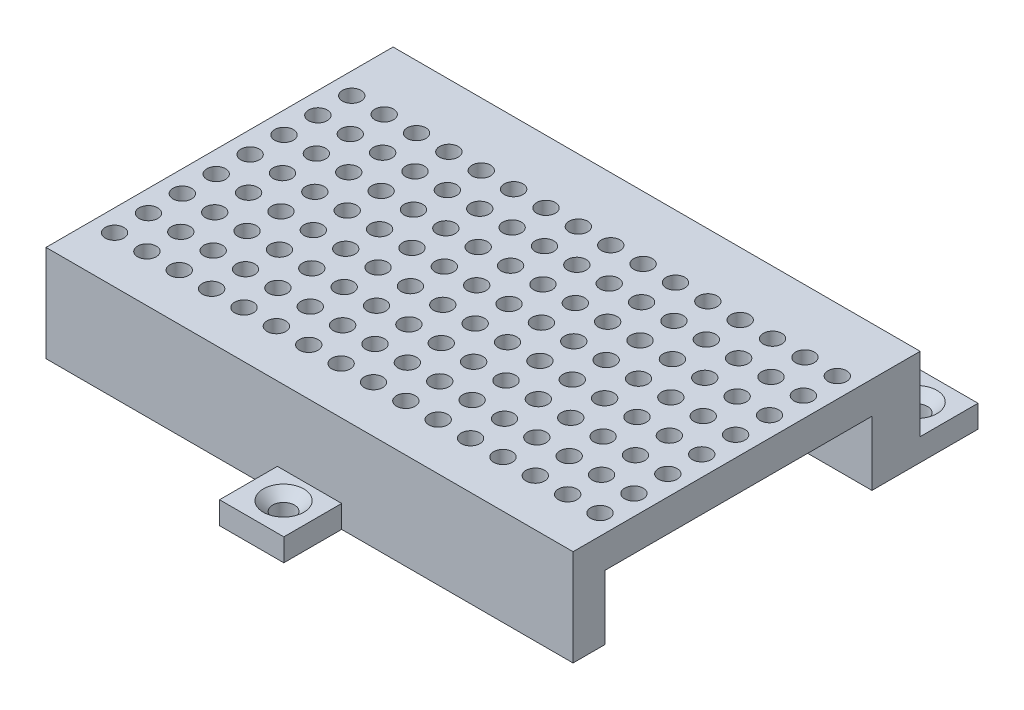
SolidWorks part; units mm, degrees
ref_plane "Plan de face" through (0, 0, 0) normal (0, 0, 1) x (1, 0, 0)
ref_plane "Plan de dessus" through (0, 0, 0) normal (0, 1, 0) x (1, 0, 0)
ref_plane "Plan de droite" through (0, 0, 0) normal (1, 0, 0) x (0, 0, -1)
sketch "Esquisse1" plane through (0, 0, 0) normal (0, 1, 0) x (1, 0, 0)
  line L1 (-43.2753, 24.8362) -> (38.7247, 24.8362)
  line L2 (-43.2753, 24.8362) -> (-43.2753, -29.1638)
  line L3 (-43.2753, -29.1638) -> (38.7247, -29.1638)
  line L4 (38.7247, 24.8362) -> (38.7247, -29.1638)
  dimension "D1" = 54
  dimension "D2" = 82
extrude "Boss.-Extru.1" add sketch "Esquisse1" along normal blind 5
sketch "Esquisse2" plane through (0, 0, 29.1638) normal (0, 0, 1) x (1, 0, 0)
  line L0 (-43.2753, 5) -> (38.7247, 5)
  line L1 (-43.2753, 5) -> (-43.2753, -10)
  line L2 (38.7247, 5) -> (38.7247, -10)
  line L3 (-43.2753, -10) -> (38.7247, -10)
  dimension "D1" = 15
extrude "Boss.-Extru.2" add sketch "Esquisse2" against normal blind 5
sketch "Esquisse3" plane through (0, 0, 0) normal (0, -1, 0) x (1, 0, 0)
  line L1 (-43.2753, -24.8362) -> (-33.2753, -24.8362)
  line L2 (-43.2753, -24.8362) -> (-43.2753, -17.3362)
  line L3 (-43.2753, -17.3362) -> (-33.2753, -17.3362)
  line L4 (-33.2753, -24.8362) -> (-33.2753, -17.3362)
  line L5 (38.7247, -24.8362) -> (28.7247, -24.8362)
  line L6 (38.7247, -24.8362) -> (38.7247, -17.3362)
  line L7 (38.7247, -17.3362) -> (28.7247, -17.3362)
  line L8 (28.7247, -24.8362) -> (28.7247, -17.3362)
  dimension "D1" = 7.5
  dimension "D2" = 10
  dimension "D3" = 7.5
  dimension "D4" = 10
extrude "Boss.-Extru.3" add sketch "Esquisse3" along normal blind 10
sketch "Esquisse4" plane through (0, 0, -24.8362) normal (0, 0, -1) x (-1, 0, 0)
  line L0 (-28.7247, -10) -> (-28.7247, 0) construction
  line L1 (-38.7247, -10) -> (-28.7247, -10)
  line L2 (-38.7247, -10) -> (-38.7247, -6.5)
  line L3 (-38.7247, -6.5) -> (-28.7247, -6.5)
  line L4 (-28.7247, -10) -> (-28.7247, -6.5)
  line L5 (33.2753, -10) -> (33.2753, 0) construction
  line L6 (43.2753, -10) -> (33.2753, -10)
  line L7 (43.2753, -10) -> (43.2753, -6.5)
  line L8 (43.2753, -6.5) -> (33.2753, -6.5)
  line L9 (33.2753, -10) -> (33.2753, -6.5)
  dimension "D1" = 3.5
  dimension "D2" = 3.5
extrude "Boss.-Extru.4" add sketch "Esquisse4" along normal blind 9
hole_wizard "Fraisage pour vis à tête fraisée M31" positions "Esquisse5" profile "Esquisse6" countersink size "M3" standard "ISO" end condition through all
sketch "Esquisse5" plane through (0, -6.5, 0) normal (0, 1, 0) x (1, 0, 0)
  point P0 (-38.4178, 29.233)
  point P2 (33.7833, 29.233)
sketch "Esquisse6" plane through (-38.4178, -6.5, -29.233) normal (1, 0, 0) x (0, 0, 1)
  line L0 (0, 0) -> (0, 3.5)
  line L1 (0, 3.5) -> (1.7, 3.5)
  line L2 (1.7, 3.5) -> (1.7, 1.45)
  line L3 (1.7, 1.45) -> (3.15, 0)
  line L5 (3.15, 0) -> (0, 0)
  line L6 (-1.7, 1.45) -> (-3.15, 0) construction
  line L11 (0, -6.35) -> (0, 107.95) construction
  dimension "Diamètre du perçage jusqu'au prochain" = 3.4
  dimension "Profondeur du perçage jusqu'au prochain" = 3.5
  dimension "Diamètre du fraisage entrant" = 6.3
  dimension "Angle du fraisage entrant" = 90
sketch "Esquisse7" plane through (0, 0, 29.1638) normal (0, 0, 1) x (1, 0, 0)
  line L1 (-43.2753, -10) -> (38.7247, -10) construction
  line L2 (38.7247, 5) -> (38.7247, -10) construction
  line L3 (-7.2753, -10) -> (2.7247, -10)
  line L4 (-7.2753, -10) -> (-7.2753, -6.5)
  line L5 (-7.2753, -6.5) -> (2.7247, -6.5)
  line L6 (2.7247, -10) -> (2.7247, -6.5)
  point P0 (-2.2753, -10)
  dimension "D1" = 36
  dimension "D2" = 10
  dimension "D3" = 3.5
extrude "Boss.-Extru.5" add sketch "Esquisse7" along normal blind 9
hole_wizard "Fraisage pour vis à tête fraisée M32" positions "Esquisse8" profile "Esquisse9" countersink size "M3" standard "ISO" end condition through all
sketch "Esquisse8" plane through (0, -6.5, 0) normal (0, 1, 0) x (1, 0, 0)
  point P0 (-2.1798, -33.2996)
sketch "Esquisse9" plane through (-2.1798, -6.5, 33.2996) normal (1, 0, 0) x (0, 0, 1)
  line L0 (0, 0) -> (0, 3.5)
  line L1 (0, 3.5) -> (1.7, 3.5)
  line L2 (1.7, 3.5) -> (1.7, 1.45)
  line L3 (1.7, 1.45) -> (3.15, 0)
  line L5 (3.15, 0) -> (0, 0)
  line L6 (-1.7, 1.45) -> (-3.15, 0) construction
  line L11 (0, -6.35) -> (0, 107.95) construction
  dimension "Diamètre du perçage jusqu'au prochain" = 3.4
  dimension "Profondeur du perçage jusqu'au prochain" = 3.5
  dimension "Diamètre du fraisage entrant" = 6.3
  dimension "Angle du fraisage entrant" = 90
sketch "Esquisse10" plane through (0, 5, 0) normal (0, 1, 0) x (1, 0, 0)
  circle A0 centre (-39.9169, 15.0522) radius 1.4509
  circle A1 centre (-34.8813, 15.0522) radius 1.4509
  circle A2 centre (-29.8456, 15.0522) radius 1.4509
  circle A3 centre (-24.81, 15.0522) radius 1.4509
  circle A4 centre (-19.7744, 15.0522) radius 1.4509
  circle A5 centre (-14.7388, 15.0522) radius 1.4509
  circle A6 centre (-9.7032, 15.0522) radius 1.4509
  circle A7 centre (-4.6675, 15.0522) radius 1.4509
  circle A8 centre (0.3681, 15.0522) radius 1.4509
  circle A9 centre (5.4037, 15.0522) radius 1.4509
  circle A10 centre (10.4393, 15.0522) radius 1.4509
  circle A11 centre (15.4749, 15.0522) radius 1.4509
  circle A12 centre (20.5106, 15.0522) radius 1.4509
  circle A13 centre (25.5462, 15.0522) radius 1.4509
  circle A14 centre (30.5818, 15.0522) radius 1.4509
  circle A15 centre (35.6174, 15.0522) radius 1.4509
  circle A16 centre (-34.8813, 9.7792) radius 1.4509
  circle A17 centre (-29.8456, 9.7792) radius 1.4509
  circle A18 centre (-24.81, 9.7792) radius 1.4509
  circle A19 centre (-19.7744, 9.7792) radius 1.4509
  circle A20 centre (-14.7388, 9.7792) radius 1.4509
  circle A21 centre (-9.7032, 9.7792) radius 1.4509
  circle A22 centre (-4.6675, 9.7792) radius 1.4509
  circle A23 centre (0.3681, 9.7792) radius 1.4509
  circle A24 centre (5.4037, 9.7792) radius 1.4509
  circle A25 centre (10.4393, 9.7792) radius 1.4509
  circle A26 centre (15.4749, 9.7792) radius 1.4509
  circle A27 centre (20.5106, 9.7792) radius 1.4509
  circle A28 centre (25.5462, 9.7792) radius 1.4509
  circle A29 centre (30.5818, 9.7792) radius 1.4509
  circle A30 centre (35.6174, 9.7792) radius 1.4509
  circle A31 centre (-34.8813, 4.5062) radius 1.4509
  circle A32 centre (-29.8456, 4.5062) radius 1.4509
  circle A33 centre (-24.81, 4.5062) radius 1.4509
  circle A34 centre (-19.7744, 4.5062) radius 1.4509
  circle A35 centre (-14.7388, 4.5062) radius 1.4509
  circle A36 centre (-9.7032, 4.5062) radius 1.4509
  circle A37 centre (-4.6675, 4.5062) radius 1.4509
  circle A38 centre (0.3681, 4.5062) radius 1.4509
  circle A39 centre (5.4037, 4.5062) radius 1.4509
  circle A40 centre (10.4393, 4.5062) radius 1.4509
  circle A41 centre (15.4749, 4.5062) radius 1.4509
  circle A42 centre (20.5106, 4.5062) radius 1.4509
  circle A43 centre (25.5462, 4.5062) radius 1.4509
  circle A44 centre (30.5818, 4.5062) radius 1.4509
  circle A45 centre (35.6174, 4.5062) radius 1.4509
  circle A46 centre (-34.8813, -0.7668) radius 1.4509
  circle A47 centre (-29.8456, -0.7668) radius 1.4509
  circle A48 centre (-24.81, -0.7668) radius 1.4509
  circle A49 centre (-19.7744, -0.7668) radius 1.4509
  circle A50 centre (-14.7388, -0.7668) radius 1.4509
  circle A51 centre (-9.7032, -0.7668) radius 1.4509
  circle A52 centre (-4.6675, -0.7668) radius 1.4509
  circle A53 centre (0.3681, -0.7668) radius 1.4509
  circle A54 centre (5.4037, -0.7668) radius 1.4509
  circle A55 centre (10.4393, -0.7668) radius 1.4509
  circle A56 centre (15.4749, -0.7668) radius 1.4509
  circle A57 centre (20.5106, -0.7668) radius 1.4509
  circle A58 centre (25.5462, -0.7668) radius 1.4509
  circle A59 centre (30.5818, -0.7668) radius 1.4509
  circle A60 centre (35.6174, -0.7668) radius 1.4509
  circle A61 centre (-34.8813, -6.0398) radius 1.4509
  circle A62 centre (-29.8456, -6.0398) radius 1.4509
  circle A63 centre (-24.81, -6.0398) radius 1.4509
  circle A64 centre (-19.7744, -6.0398) radius 1.4509
  circle A65 centre (-14.7388, -6.0398) radius 1.4509
  circle A66 centre (-9.7032, -6.0398) radius 1.4509
  circle A67 centre (-4.6675, -6.0398) radius 1.4509
  circle A68 centre (0.3681, -6.0398) radius 1.4509
  circle A69 centre (5.4037, -6.0398) radius 1.4509
  circle A70 centre (10.4393, -6.0398) radius 1.4509
  circle A71 centre (15.4749, -6.0398) radius 1.4509
  circle A72 centre (20.5106, -6.0398) radius 1.4509
  circle A73 centre (25.5462, -6.0398) radius 1.4509
  circle A74 centre (30.5818, -6.0398) radius 1.4509
  circle A75 centre (35.6174, -6.0398) radius 1.4509
  circle A76 centre (-34.8813, -11.3129) radius 1.4509
  circle A77 centre (-29.8456, -11.3129) radius 1.4509
  circle A78 centre (-24.81, -11.3129) radius 1.4509
  circle A79 centre (-19.7744, -11.3129) radius 1.4509
  circle A80 centre (-14.7388, -11.3129) radius 1.4509
  circle A81 centre (-9.7032, -11.3129) radius 1.4509
  circle A82 centre (-4.6675, -11.3129) radius 1.4509
  circle A83 centre (0.3681, -11.3129) radius 1.4509
  circle A84 centre (5.4037, -11.3129) radius 1.4509
  circle A85 centre (10.4393, -11.3129) radius 1.4509
  circle A86 centre (15.4749, -11.3129) radius 1.4509
  circle A87 centre (20.5106, -11.3129) radius 1.4509
  circle A88 centre (25.5462, -11.3129) radius 1.4509
  circle A89 centre (30.5818, -11.3129) radius 1.4509
  circle A90 centre (35.6174, -11.3129) radius 1.4509
  circle A91 centre (-34.8813, -16.5859) radius 1.4509
  circle A92 centre (-29.8456, -16.5859) radius 1.4509
  circle A93 centre (-24.81, -16.5859) radius 1.4509
  circle A94 centre (-19.7744, -16.5859) radius 1.4509
  circle A95 centre (-14.7388, -16.5859) radius 1.4509
  circle A96 centre (-9.7032, -16.5859) radius 1.4509
  circle A97 centre (-4.6675, -16.5859) radius 1.4509
  circle A98 centre (0.3681, -16.5859) radius 1.4509
  circle A99 centre (5.4037, -16.5859) radius 1.4509
  circle A100 centre (10.4393, -16.5859) radius 1.4509
  circle A101 centre (15.4749, -16.5859) radius 1.4509
  circle A102 centre (20.5106, -16.5859) radius 1.4509
  circle A103 centre (25.5462, -16.5859) radius 1.4509
  circle A104 centre (30.5818, -16.5859) radius 1.4509
  circle A105 centre (35.6174, -16.5859) radius 1.4509
  circle A106 centre (-34.8813, -21.8589) radius 1.4509
  circle A107 centre (-29.8456, -21.8589) radius 1.4509
  circle A108 centre (-24.81, -21.8589) radius 1.4509
  circle A109 centre (-19.7744, -21.8589) radius 1.4509
  circle A110 centre (-14.7388, -21.8589) radius 1.4509
  circle A111 centre (-9.7032, -21.8589) radius 1.4509
  circle A112 centre (-4.6675, -21.8589) radius 1.4509
  circle A113 centre (0.3681, -21.8589) radius 1.4509
  circle A114 centre (5.4037, -21.8589) radius 1.4509
  circle A115 centre (10.4393, -21.8589) radius 1.4509
  circle A116 centre (15.4749, -21.8589) radius 1.4509
  circle A117 centre (20.5106, -21.8589) radius 1.4509
  circle A118 centre (25.5462, -21.8589) radius 1.4509
  circle A119 centre (30.5818, -21.8589) radius 1.4509
  circle A120 centre (35.6174, -21.8589) radius 1.4509
  circle A136 centre (-39.9169, 9.7792) radius 1.4509
  circle A137 centre (-39.9169, 4.5062) radius 1.4509
  circle A138 centre (-39.9169, -0.7668) radius 1.4509
  circle A139 centre (-39.9169, -6.0398) radius 1.4509
  circle A140 centre (-39.9169, -11.3129) radius 1.4509
  circle A141 centre (-39.9169, -16.5859) radius 1.4509
  circle A142 centre (-39.9169, -21.8589) radius 1.4509
  circle A144 centre (-34.8813, -27.1319) radius 1.4509 [skipped]
  circle A145 centre (-29.8456, -27.1319) radius 1.4509 [skipped]
  circle A146 centre (-24.81, -27.1319) radius 1.4509 [skipped]
  circle A147 centre (-19.7744, -27.1319) radius 1.4509 [skipped]
  circle A148 centre (-14.7388, -27.1319) radius 1.4509 [skipped]
  circle A149 centre (-9.7032, -27.1319) radius 1.4509 [skipped]
  circle A150 centre (-4.6675, -27.1319) radius 1.4509 [skipped]
  circle A151 centre (0.3681, -27.1319) radius 1.4509 [skipped]
  circle A152 centre (5.4037, -27.1319) radius 1.4509 [skipped]
  circle A153 centre (10.4393, -27.1319) radius 1.4509 [skipped]
  circle A154 centre (15.4749, -27.1319) radius 1.4509 [skipped]
  circle A155 centre (20.5106, -27.1319) radius 1.4509 [skipped]
  circle A156 centre (25.5462, -27.1319) radius 1.4509 [skipped]
  circle A157 centre (30.5818, -27.1319) radius 1.4509 [skipped]
  circle A158 centre (35.6174, -27.1319) radius 1.4509 [skipped]
  circle A159 centre (-39.9169, -27.1319) radius 1.4509 [skipped]
  point P2 (-39.5596, 7.3252)
  point P3 (-4.663, 1.4656)
  point P4 (-39.7091, 5.051)
  point P245 (0, 0)
  point P246 (15.6827, -21.287)
  point P247 (0, 0)
  point P248 (-39.9169, 9.7792)
  dimension "D1" = 16
  dimension "D2" = 9
extrude "Enlèv. mat.-Extru.1" cut sketch "Esquisse10" against normal blind 9
